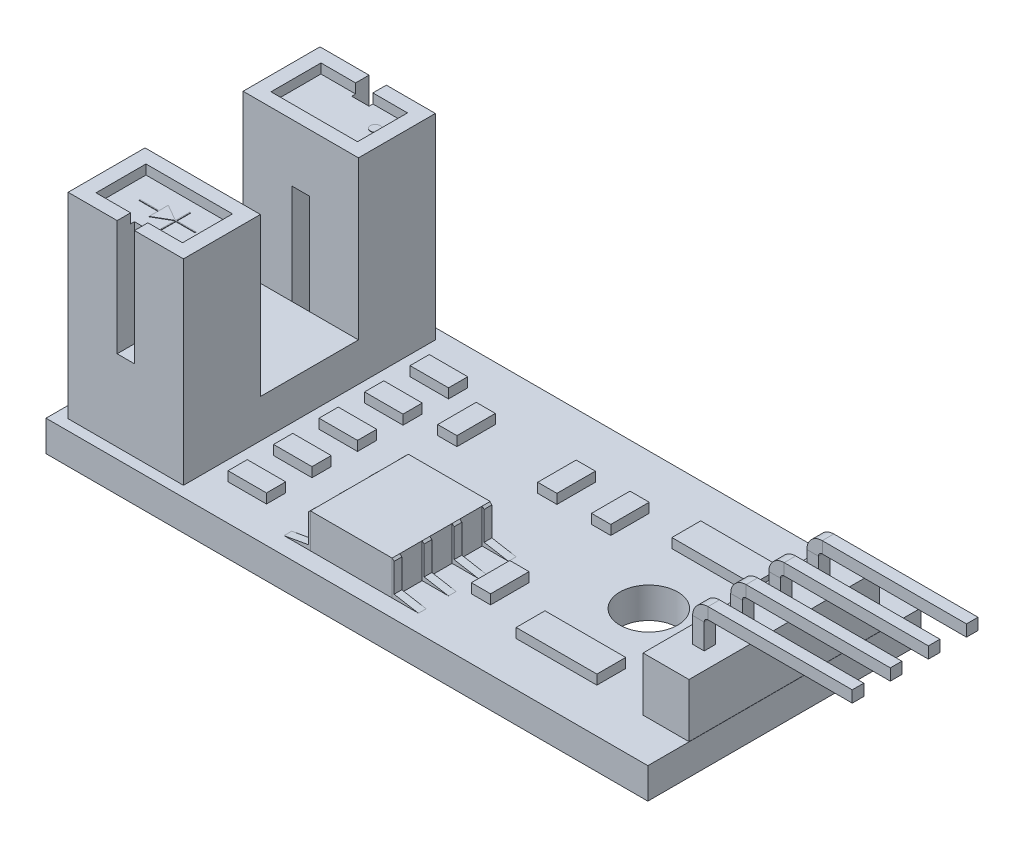
SolidWorks part; units mm, degrees
ref_plane "Front Plane" through (0, 0, 0) normal (0, 0, 1) x (1, 0, 0)
ref_plane "Top Plane" through (0, 0, 0) normal (0, 1, 0) x (1, 0, 0)
ref_plane "Right Plane" through (0, 0, 0) normal (1, 0, 0) x (0, 0, -1)
sketch "Sketch1" plane through (0, 0, 0) normal (0, 1, 0) x (1, 0, 0)
  line L1 (-15.65, 7.1) -> (15.65, 7.1)
  line L2 (-15.65, 7.1) -> (-15.65, -7.1)
  line L3 (-15.65, -7.1) -> (15.65, -7.1)
  line L4 (15.65, 7.1) -> (15.65, -7.1)
  line L5 (-15.65, 7.1) -> (15.65, -7.1) construction
  line L6 (-15.65, -7.1) -> (15.65, 7.1) construction
  point P0 (0, 0)
  dimension "D1" = 14.2
  dimension "D2" = 31.3
extrude "Boss-Extrude1" add sketch "Sketch1" along normal mid plane 1.6
sketch "Sketch2" plane through (0, 0.8, 0) normal (0, 1, 0) x (1, 0, 0)
  line L0 (-15.65, 7.1) -> (-15.65, -7.1) construction
  line L1 (-15.05, 6.55) -> (-9.05, 6.55)
  line L2 (-15.05, 6.55) -> (-15.05, -6.55)
  line L3 (-15.05, -6.55) -> (-9.05, -6.55)
  line L4 (-9.05, 6.55) -> (-9.05, -6.55)
  line L5 (-15.05, 6.55) -> (-9.05, -6.55) construction
  line L6 (-15.05, -6.55) -> (-9.05, 6.55) construction
  point P0 (-12.05, 0)
  dimension "D1" = 13.1
  dimension "D2" = 6
  dimension "D3" = 0.6
extrude "Boss-Extrude2" add sketch "Sketch2" along normal blind 2
sketch "Sketch3" plane through (0, 2.8, 0) normal (0, 1, 0) x (1, 0, 0)
  line L0 (-15.05, -6.55) -> (-9.05, -6.55) construction
  line L1 (-15.05, -2.55) -> (-9.05, -2.55)
  line L2 (-15.05, -2.55) -> (-15.05, -6.55)
  line L3 (-15.05, -6.55) -> (-9.05, -6.55)
  line L4 (-9.05, -2.55) -> (-9.05, -6.55)
  line L5 (-15.05, -2.55) -> (-9.05, -6.55) construction
  line L6 (-15.05, -6.55) -> (-9.05, -2.55) construction
  line L7 (-15.05, 6.55) -> (-15.05, -6.55) construction
  line L8 (-15.05, 6.55) -> (-9.05, 6.55)
  line L9 (-15.05, 6.55) -> (-15.05, 2.55)
  line L10 (-15.05, 2.55) -> (-9.05, 2.55)
  line L11 (-9.05, 6.55) -> (-9.05, 2.55)
  line L12 (-15.05, 6.55) -> (-9.05, 2.55) construction
  line L13 (-15.05, 2.55) -> (-9.05, 6.55) construction
  line L14 (-9.05, 6.55) -> (-15.05, 6.55) construction
  point P0 (-12.05, -4.55)
  point P9 (-12.05, 4.55)
  dimension "D1" = 4
  dimension "D2" = 6
  dimension "D3" = 4
  dimension "D4" = 6
extrude "Boss-Extrude3" add sketch "Sketch3" along normal blind 8.2
sketch "Sketch4" plane through (0, 0, 6.55) normal (0, 0, 1) x (1, 0, 0)
  line L0 (-15.05, 11) -> (-9.05, 11) construction
  line L1 (-12.5, 11) -> (-11.6, 11)
  line L2 (-12.5, 11) -> (-12.5, 5)
  line L3 (-12.5, 5) -> (-11.6, 5)
  line L4 (-11.6, 11) -> (-11.6, 5)
  line L5 (-12.5, 11) -> (-11.6, 5) construction
  line L6 (-12.5, 5) -> (-11.6, 11) construction
  point P0 (-12.05, 8)
  point P9 (-12.05, 11)
  dimension "D1" = 6
  dimension "D2" = 0.9
extrude "Cut-Extrude1" cut sketch "Sketch4" against normal blind 0.9
mirror "Mirror1" about plane through (0, 0, 0) normal (0, 0, 1) of "Cut-Extrude1"
sketch "Sketch5" plane through (0, 0, 2.55) normal (0, 0, -1) x (-1, 0, 0)
  line L0 (12.05, 11) -> (12.05, 8) construction
  line L1 (11.6, 11) -> (12.5, 11) construction
  line L2 (9.05, 0.8) -> (15.05, 0.8) construction
  line L3 (11.6, 0.8) -> (12.5, 0.8)
  line L4 (11.6, 0.8) -> (11.6, 8)
  line L5 (11.6, 8) -> (12.5, 8)
  line L6 (12.5, 0.8) -> (12.5, 8)
  line L7 (11.6, 0.8) -> (12.5, 8) construction
  line L8 (11.6, 8) -> (12.5, 0.8) construction
  point P4 (12.05, 4.4)
  dimension "D1" = 3
  dimension "D2" = 0.9
extrude "Cut-Extrude2" cut sketch "Sketch5" against normal blind 0.9
mirror "Mirror2" about plane through (0, 0, 0) normal (0, 0, 1) of "Cut-Extrude2"
sketch "Sketch6" plane through (0, 11, 0) normal (0, 1, 0) x (1, 0, 0)
  line L0 (-15.05, 6.55) -> (-9.05, 2.55) construction
  line L1 (-14.3, 5.85) -> (-9.8, 5.85)
  line L2 (-14.3, 5.85) -> (-14.3, 3.25)
  line L3 (-14.3, 3.25) -> (-9.8, 3.25)
  line L4 (-9.8, 5.85) -> (-9.8, 3.25)
  line L5 (-14.3, 5.85) -> (-9.8, 3.25) construction
  line L6 (-14.3, 3.25) -> (-9.8, 5.85) construction
  line L7 (-15.05, -2.55) -> (-9.05, -6.55) construction
  line L8 (-14.3, -3.25) -> (-9.8, -3.25)
  line L9 (-14.3, -3.25) -> (-14.3, -5.85)
  line L10 (-14.3, -5.85) -> (-9.8, -5.85)
  line L11 (-9.8, -3.25) -> (-9.8, -5.85)
  line L12 (-14.3, -3.25) -> (-9.8, -5.85) construction
  line L13 (-14.3, -5.85) -> (-9.8, -3.25) construction
  point P0 (-12.05, 4.55)
  point P11 (-12.05, -4.55)
  dimension "D1" = 2.6
  dimension "D2" = 4.5
  dimension "D3" = 2.6
  dimension "D4" = 4.5
extrude "Cut-Extrude3" cut sketch "Sketch6" against normal blind 0.5
sketch "Sketch7" plane through (0, -0.8, 0) normal (0, -1, 0) x (1, 0, 0)
  line L0 (-15.65, -7.1) -> (-15.65, 7.1) construction
  line L1 (-15.65, 0) -> (7.1, 0) construction
  circle A0 centre (8.6, 0) radius 1.5
  dimension "D1" = 3
  dimension "D2" = 22.75
extrude "Cut-Extrude4" cut sketch "Sketch7" against normal through all both and the other way through all
sketch "Sketch8" plane through (0, 0.8, 0) normal (0, 1, 0) x (1, 0, 0)
  line L0 (15.65, -7.1) -> (15.65, 7.1) construction
  line L1 (13.25, 4.95) -> (15.65, 4.95)
  line L2 (13.25, 4.95) -> (13.25, -4.95)
  line L3 (13.25, -4.95) -> (15.65, -4.95)
  line L4 (15.65, 4.95) -> (15.65, -4.95)
  line L5 (13.25, 4.95) -> (15.65, -4.95) construction
  line L6 (13.25, -4.95) -> (15.65, 4.95) construction
  point P0 (14.45, 0)
  dimension "D1" = 9.9
  dimension "D2" = 2.4
extrude "Boss-Extrude4" add sketch "Sketch8" along normal blind 2.8 separate body
sketch "Sketch9" plane through (0, 0.8, 0) normal (0, 1, 0) x (1, 0, 0)
  line L0 (-15.65, -7.1) -> (15.65, -7.1) construction
  line L1 (-2.8, -1.1) -> (1.45, -1.1)
  line L2 (-2.8, -1.1) -> (-2.8, -6.2)
  line L3 (-2.8, -6.2) -> (1.45, -6.2)
  line L4 (1.45, -1.1) -> (1.45, -6.2)
  line L5 (-2.8, -1.1) -> (1.45, -6.2) construction
  line L6 (-2.8, -6.2) -> (1.45, -1.1) construction
  line L7 (-9.05, -6.55) -> (-9.05, -2.55) construction
  point P0 (-0.675, -3.65)
  dimension "D1" = 5.1
  dimension "D2" = 4.25
  dimension "D3" = 0.9
  dimension "D4" = 6.25
extrude "Boss-Extrude5" add sketch "Sketch9" along normal blind 1.8
sketch "Sketch10" plane through (0, 3.6, 0) normal (0, 1, 0) x (1, 0, 0)
  line L0 (14.45, -4.95) -> (14.45, -2.97) construction
  line L1 (13.25, -4.95) -> (15.65, -4.95) construction
  line L2 (14.45, -2.97) -> (14.45, -0.99) construction
  line L3 (14.15, 3.27) -> (14.75, 3.27)
  line L4 (14.15, 1.29) -> (14.75, 1.29)
  line L5 (14.15, 1.29) -> (14.15, 0.69)
  line L6 (14.15, 0.69) -> (14.75, 0.69)
  line L7 (14.75, 1.29) -> (14.75, 0.69)
  line L8 (14.15, 1.29) -> (14.75, 0.69) construction
  line L9 (14.15, 0.69) -> (14.75, 1.29) construction
  line L10 (14.15, 3.27) -> (14.15, 2.67)
  line L11 (14.15, 2.67) -> (14.75, 2.67)
  line L12 (14.75, 3.27) -> (14.75, 2.67)
  line L13 (14.15, 3.27) -> (14.75, 2.67) construction
  line L14 (14.15, 2.67) -> (14.75, 3.27) construction
  line L15 (14.15, -2.67) -> (14.75, -2.67)
  line L16 (14.15, -2.67) -> (14.15, -3.27)
  line L17 (14.15, -3.27) -> (14.75, -3.27)
  line L18 (14.75, -2.67) -> (14.75, -3.27)
  line L19 (14.15, -2.67) -> (14.75, -3.27) construction
  line L20 (14.15, -3.27) -> (14.75, -2.67) construction
  line L21 (14.15, -0.69) -> (14.75, -0.69)
  line L22 (14.15, -0.69) -> (14.15, -1.29)
  line L23 (14.15, -1.29) -> (14.75, -1.29)
  line L24 (14.75, -0.69) -> (14.75, -1.29)
  line L25 (14.15, -0.69) -> (14.75, -1.29) construction
  line L26 (14.15, -1.29) -> (14.75, -0.69) construction
  line L28 (14.45, -0.99) -> (14.45, 0.99) construction
  line L29 (14.45, 0.99) -> (14.45, 2.97) construction
  line L30 (14.45, 2.97) -> (14.45, 4.95) construction
  line L31 (15.65, 4.95) -> (13.25, 4.95) construction
  point P6 (14.45, 0.99)
  point P11 (14.45, 2.97)
  point P16 (14.45, -2.97)
  point P21 (14.45, -0.99)
  dimension "D1" = 0.6
  dimension "D2" = 0.6
  dimension "D3" = 0.6
  dimension "D4" = 0.6
extrude "Cut-Extrude5" cut sketch "Sketch10" against normal through all both and the other way through all
sketch "Sketch11" plane through (0, 10.5, 0) normal (0, 1, 0) x (1, 0, 0)
  line L0 (-14.3, -5.85) -> (-9.8, -3.25) construction
  line L1 (-13.3387, -4.575) -> (-12.3387, -4.575)
  line L2 (-13.3387, -4.575) -> (-13.3387, -4.525)
  line L3 (-13.3387, -4.525) -> (-12.3387, -4.525)
  line L5 (-13.3387, -4.575) -> (-12.3387, -4.525) construction
  line L6 (-13.3387, -4.525) -> (-12.3387, -4.575) construction
  line L7 (-11.4905, -4.5397) -> (-12.3387, -4.05)
  line L8 (-12.3387, -4.05) -> (-12.3387, -4.525)
  line L9 (-12.3387, -5.05) -> (-11.4905, -4.5603)
  line L10 (-11.4226, -3.8) -> (-11.4726, -3.8)
  line L11 (-11.4226, -3.8) -> (-11.4226, -4.525)
  line L12 (-11.4226, -5.3) -> (-11.4726, -5.3)
  line L13 (-11.4726, -3.8) -> (-11.4726, -4.5397)
  line L14 (-11.4226, -3.8) -> (-11.4726, -5.3) construction
  line L15 (-11.4226, -5.3) -> (-11.4726, -3.8) construction
  line L16 (-10.4226, -4.525) -> (-11.4226, -4.525)
  line L17 (-10.4226, -4.525) -> (-10.4226, -4.575)
  line L18 (-10.4226, -4.575) -> (-11.4226, -4.575)
  line L20 (-10.4226, -4.525) -> (-11.4226, -4.575) construction
  line L21 (-10.4226, -4.575) -> (-11.4226, -4.525) construction
  line L22 (-11.4226, -4.575) -> (-11.4226, -5.3)
  line L23 (-12.3387, -4.575) -> (-12.3387, -5.05)
  line L24 (-11.4905, -4.5397) -> (-11.4726, -4.5397)
  line L25 (-11.4905, -4.5603) -> (-11.4726, -4.5603)
  line L26 (-11.4726, -4.5603) -> (-11.4726, -5.3)
  circle A0 centre (-12.05, -4.55) radius 0.2887 construction
  circle A1 centre (-10.4226, 4.7971) radius 0.25
  point P0 (-12.8387, -4.55)
  point P12 (-11.4476, -4.55)
  point P18 (-10.9226, -4.55)
  dimension "D4" = 0.5
  dimension "D1" = 1
  dimension "D2" = 0.05
  dimension "D3" = 1.5
extrude "Boss-Extrude11" add sketch "Sketch11" along normal blind 0.02
sketch "Sketch15" plane through (0, 0, 6.2) normal (0, 0, 1) x (1, 0, 0)
  line L0 (1.45, 0.8) -> (1.45, 2.6)
  line L1 (-15.65, 0.8) -> (15.65, 0.8) construction
  line L2 (1.45, 2.6) -> (1.45, 0.8) construction
  line L3 (-2.8, 2.6) -> (1.45, 2.6) construction
  line L4 (1.45, 2.6) -> (1.5556, 2.5036)
  line L5 (1.5556, 2.5036) -> (1.5556, 1.0228)
  line L6 (1.5556, 1.0228) -> (2.8211, 0.8)
  line L7 (2.8211, 0.8) -> (1.45, 0.8)
  line L8 (-0.675, 0.8) -> (-0.675, 2.6) construction
  line L9 (-2.8, 0.8) -> (1.45, 0.8) construction
  line L10 (-4.1711, 0.8) -> (-2.8, 0.8)
  line L11 (-2.9056, 1.0228) -> (-4.1711, 0.8)
  line L12 (-2.9056, 2.5036) -> (-2.9056, 1.0228)
  line L13 (-2.8, 2.6) -> (-2.9056, 2.5036)
  line L14 (-2.8, 0.8) -> (-2.8, 2.6)
extrude "Boss-Extrude14" add sketch "Sketch15" against normal blind 0.4 separate body
pattern_linear "LPattern1" count 4 spacing 1.56 along (0, 0, -1) of "Boss-Extrude14"
sketch "Sketch16" plane through (0, 0.8, 0) normal (0, 1, 0) x (1, 0, 0)
  line L0 (-8.05, -1.8667) -> (-6.05, -1.8667)
  line L1 (-8.05, -4.2333) -> (-6.05, -4.2333)
  line L2 (-8.05, -4.2333) -> (-8.05, -5.2333)
  line L3 (-8.05, -5.2333) -> (-6.05, -5.2333)
  line L4 (-6.05, -4.2333) -> (-6.05, -5.2333)
  line L5 (-8.05, -4.2333) -> (-6.05, -5.2333) construction
  line L6 (-8.05, -5.2333) -> (-6.05, -4.2333) construction
  line L7 (-8.05, -1.8667) -> (-8.05, -2.8667)
  line L8 (-8.05, -2.8667) -> (-6.05, -2.8667)
  line L9 (-6.05, -1.8667) -> (-6.05, -2.8667)
  line L10 (-8.05, -1.8667) -> (-6.05, -2.8667) construction
  line L11 (-8.05, -2.8667) -> (-6.05, -1.8667) construction
  line L12 (-8.05, 0.5) -> (-6.05, 0.5)
  line L13 (-8.05, 0.5) -> (-8.05, -0.5)
  line L14 (-8.05, -0.5) -> (-6.05, -0.5)
  line L15 (-6.05, 0.5) -> (-6.05, -0.5)
  line L16 (-8.05, 0.5) -> (-6.05, -0.5) construction
  line L17 (-8.05, -0.5) -> (-6.05, 0.5) construction
  line L18 (-8.05, 2.8667) -> (-6.05, 2.8667)
  line L19 (-8.05, 2.8667) -> (-8.05, 1.8667)
  line L20 (-8.05, 1.8667) -> (-6.05, 1.8667)
  line L21 (-6.05, 2.8667) -> (-6.05, 1.8667)
  line L22 (-8.05, 2.8667) -> (-6.05, 1.8667) construction
  line L23 (-8.05, 1.8667) -> (-6.05, 2.8667) construction
  line L24 (-8.05, 5.2333) -> (-6.05, 5.2333)
  line L25 (-8.05, 5.2333) -> (-8.05, 4.2333)
  line L26 (-8.05, 4.2333) -> (-6.05, 4.2333)
  line L27 (-6.05, 5.2333) -> (-6.05, 4.2333)
  line L28 (-8.05, 5.2333) -> (-6.05, 4.2333) construction
  line L29 (-8.05, 4.2333) -> (-6.05, 5.2333) construction
  line L30 (-7.05, 7.1) -> (-7.05, 4.7333) construction
  line L31 (15.65, 7.1) -> (-15.65, 7.1) construction
  line L32 (-7.05, 4.7333) -> (-7.05, 2.3667) construction
  line L33 (-7.05, 2.3667) -> (-7.05, 0) construction
  line L34 (-7.05, 0) -> (-7.05, -2.3667) construction
  line L35 (-7.05, -2.3667) -> (-7.05, -4.7333) construction
  line L36 (-7.05, -4.7333) -> (-7.05, -7.1) construction
  line L37 (-15.65, -7.1) -> (15.65, -7.1) construction
  line L38 (-9.05, -6.55) -> (-9.05, -2.55) construction
  line L39 (0.5211, 4.3) -> (1.5211, 4.3)
  line L40 (-4.6789, 4.3) -> (-3.6789, 4.3)
  line L41 (-4.6789, 4.3) -> (-4.6789, 2.3)
  line L42 (-4.6789, 2.3) -> (-3.6789, 2.3)
  line L43 (-3.6789, 4.3) -> (-3.6789, 2.3)
  line L44 (-4.6789, 4.3) -> (-3.6789, 2.3) construction
  line L45 (-4.6789, 2.3) -> (-3.6789, 4.3) construction
  line L46 (0.5211, 4.3) -> (0.5211, 2.3)
  line L47 (0.5211, 2.3) -> (1.5211, 2.3)
  line L48 (1.5211, 4.3) -> (1.5211, 2.3)
  line L49 (0.5211, 4.3) -> (1.5211, 2.3) construction
  line L50 (0.5211, 2.3) -> (1.5211, 4.3) construction
  line L51 (3.3211, 4.3) -> (4.3211, 4.3)
  line L52 (3.3211, 4.3) -> (3.3211, 2.3)
  line L53 (3.3211, 2.3) -> (4.3211, 2.3)
  line L54 (4.3211, 4.3) -> (4.3211, 2.3)
  line L55 (3.3211, 4.3) -> (4.3211, 2.3) construction
  line L56 (3.3211, 2.3) -> (4.3211, 4.3) construction
  line L57 (3.3211, -1.95) -> (4.3211, -1.95)
  line L58 (3.3211, -1.95) -> (3.3211, -3.95)
  line L59 (3.3211, -3.95) -> (4.3211, -3.95)
  line L60 (4.3211, -1.95) -> (4.3211, -3.95)
  line L61 (3.3211, -1.95) -> (4.3211, -3.95) construction
  line L62 (3.3211, -3.95) -> (4.3211, -1.95) construction
  line L63 (3.8211, -2.95) -> (3.8211, 3.3) construction
  line L64 (1.0211, 3.3) -> (3.8211, 3.3) construction
  line L65 (1.0211, 3.3) -> (-4.1789, 3.3) construction
  line L66 (2.8211, -2.68) -> (2.8211, -3.08) construction
  line L67 (6.5, -3.3) -> (10.7, -3.3)
  line L68 (6.5, 4.8) -> (10.7, 4.8)
  line L69 (6.5, 4.8) -> (6.5, 3.3)
  line L70 (6.5, 3.3) -> (10.7, 3.3)
  line L71 (10.7, 4.8) -> (10.7, 3.3)
  line L72 (6.5, 4.8) -> (10.7, 3.3) construction
  line L73 (6.5, 3.3) -> (10.7, 4.8) construction
  line L74 (6.5, -3.3) -> (6.5, -4.8)
  line L75 (6.5, -4.8) -> (10.7, -4.8)
  line L76 (10.7, -3.3) -> (10.7, -4.8)
  line L77 (6.5, -3.3) -> (10.7, -4.8) construction
  line L78 (6.5, -4.8) -> (10.7, -3.3) construction
  line L79 (8.6, 0) -> (8.6, 7.1) construction
  point P0 (-7.05, -4.7333)
  point P6 (-7.05, -2.3667)
  point P11 (-7.05, 0)
  point P16 (-7.05, 2.3667)
  point P21 (-7.05, 4.7333)
  point P37 (1.0211, 3.3)
  point P40 (-4.1789, 3.3)
  point P49 (3.8211, 3.3)
  point P54 (8.6, -4.05)
  point P56 (3.8211, -2.95)
  point P65 (8.6, 4.05)
  dimension "D1" = 1
  dimension "D2" = 2
  dimension "D3" = 1
  dimension "D4" = 2
  dimension "D5" = 1
  dimension "D6" = 2
  dimension "D7" = 1
  dimension "D8" = 2
  dimension "D9" = 1
  dimension "D10" = 2
  dimension "D11" = 1
  dimension "D12" = 2
  dimension "D13" = 1
  dimension "D14" = 2
  dimension "D15" = 1
  dimension "D16" = 2
  dimension "D17" = 1
  dimension "D18" = 2
  dimension "D19" = 1
  dimension "D20" = 6.25
  dimension "D21" = 2.8
  dimension "D22" = 1.8
  dimension "D23" = 4.2
  dimension "D24" = 0.5
  dimension "D25" = 1.5
  dimension "D26" = 4.2
  dimension "D27" = 1.5
  dimension "D28" = 4.2
  dimension "D29" = 3.8
  dimension "D30" = 3.8
extrude "Boss-Extrude15" add sketch "Sketch16" along normal blind 0.5
sketch "Sketch17" plane through (0, -0.8, 0) normal (0, -1, 0) x (1, 0, 0)
  line L0 (-13.65, 5.1) -> (-15.65, 5.1) construction
  line L1 (-13.65, 5.8) -> (-12.25, 5.8)
  line L2 (-13.65, 5.8) -> (-13.65, 4.4)
  line L3 (-13.65, 4.4) -> (-12.25, 4.4)
  line L4 (-12.25, 5.8) -> (-12.25, 4.4)
  line L5 (-13.65, 5.8) -> (-12.25, 4.4) construction
  line L6 (-13.65, 4.4) -> (-12.25, 5.8) construction
  line L7 (-15.65, -7.1) -> (-15.65, 7.1) construction
  line L8 (-12.95, 5.1) -> (-10.55, 5.1) construction
  line L9 (-15.65, 7.1) -> (15.65, 7.1) construction
  line L10 (-11.25, 5.8) -> (-9.85, 5.8)
  line L11 (-11.25, 5.8) -> (-11.25, 4.4)
  line L12 (-11.25, 4.4) -> (-9.85, 4.4)
  line L13 (-9.85, 5.8) -> (-9.85, 4.4)
  line L14 (-11.25, 5.8) -> (-9.85, 4.4) construction
  line L15 (-11.25, 4.4) -> (-9.85, 5.8) construction
  line L16 (0, 0) -> (-15.65, 0) construction
  line L17 (-11.25, -4.4) -> (-9.85, -5.8) construction
  line L18 (-11.25, -5.8) -> (-9.85, -4.4) construction
  line L19 (-12.95, -5.1) -> (-10.55, -5.1) construction
  line L20 (-13.65, -4.4) -> (-12.25, -5.8) construction
  line L21 (-13.65, -5.8) -> (-12.25, -4.4) construction
  line L22 (-13.65, -5.1) -> (-15.65, -5.1) construction
  line L23 (-9.85, -5.8) -> (-9.85, -4.4)
  line L24 (-11.25, -4.4) -> (-9.85, -4.4)
  line L25 (-11.25, -5.8) -> (-11.25, -4.4)
  line L26 (-11.25, -5.8) -> (-9.85, -5.8)
  line L27 (-12.25, -5.8) -> (-12.25, -4.4)
  line L28 (-13.65, -4.4) -> (-12.25, -4.4)
  line L29 (-13.65, -5.8) -> (-13.65, -4.4)
  line L30 (-13.65, -5.8) -> (-12.25, -5.8)
  point P0 (-12.95, 5.1)
  point P11 (-10.55, 5.1)
  dimension "D1" = 1.4
  dimension "D2" = 1.4
  dimension "D3" = 2.7
  dimension "D4" = 3.8
  dimension "D5" = 5.8
extrude "Cut-Extrude6" cut sketch "Sketch17" against normal up to surface (1.6 mm away) up to face at (-0.675, 0.8, 2.99)
sketch "Sketch18" plane through (0, 3.6, 0) normal (0, 1, 0) x (1, 0, 0)
  line L0 (14.15, -2.67) -> (14.75, -3.27) construction
  line L2 (14.15, -3.27) -> (14.75, -3.27)
  line L3 (14.15, -3.27) -> (14.15, -2.67)
  line L4 (14.15, -2.67) -> (14.75, -2.67)
  line L5 (14.75, -3.27) -> (14.75, -2.67)
  line L6 (14.15, -3.27) -> (14.75, -2.67) construction
  line L7 (14.15, -2.67) -> (14.75, -3.27) construction
  point P4 (14.45, -2.97)
ref_plane "Plane1" through (0, 0, 2.97) normal (0, 0, 1) x (1, 0, 0)
sketch "Sketch19" plane through (0, 0, 2.97) normal (0, 0, 1) x (1, 0, 0)
  line L0 (14.45, 3.6) -> (14.45, 4.9)
  line L1 (14.95, 5.4) -> (22.45, 5.4)
  line L2 (14.45, 3.6) -> (14.45, -1.3)
  line L4 (-15.65, -0.8) -> (15.65, -0.8) construction
  arc A0 (14.45, 4.9) -> (14.95, 5.4) centre (14.95, 4.9) cw
  point P7 (14.45, 5.4)
  dimension "D2" = 0.5
  dimension "D1" = 8
  dimension "D3" = 1.8
  dimension "D4" = 0.5
sweep "Sweep2" add profiles "Sketch18" path "Sketch19"
mirror "Mirror3" about plane through (0, 0, 0) normal (0, 0, 1) of "Sweep2"
sketch "Sketch20" plane through (15.65, 0, 0) normal (1, 0, 0) x (0, 0, -1)
  line L0 (4.95, 3.6) -> (-4.95, 3.6)
  line L1 (-4.95, 3.6) -> (-4.95, 0.8)
  line L2 (-4.95, 3.6) -> (-4.95, 0.8) construction
  line L3 (-4.95, 0.8) -> (4.95, 0.8)
  line L4 (4.95, 0.8) -> (4.95, 3.6)
extrude "Cut-Extrude7" cut sketch "Sketch20" against normal blind 0.01
sketch "Sketch21" plane through (0, 3.6, 0) normal (0, 1, 0) x (1, 0, 0)
  line L0 (14.15, -0.69) -> (14.75, -1.29) construction
  line L2 (14.15, -1.29) -> (14.75, -1.29)
  line L3 (14.15, -1.29) -> (14.15, -0.69)
  line L4 (14.15, -0.69) -> (14.75, -0.69)
  line L5 (14.75, -1.29) -> (14.75, -0.69)
  line L6 (14.15, -1.29) -> (14.75, -0.69) construction
  line L7 (14.15, -0.69) -> (14.75, -1.29) construction
  point P4 (14.45, -0.99)
ref_plane "Plane2" through (0, 0, 0.99) normal (0, 0, 1) x (1, 0, 0)
sketch "Sketch22" plane through (0, 0, 0.99) normal (0, 0, 1) x (1, 0, 0)
  line L0 (14.45, -1.3) -> (14.45, 4.9)
  line L1 (14.15, -1.3) -> (14.75, -1.3) construction
  line L2 (14.95, 5.4) -> (22.45, 5.4)
  line L3 (22.45, 5.7) -> (22.45, 5.1) construction
  line L4 (13.25, 3.6) -> (15.64, 3.6) construction
  arc A0 (14.95, 5.4) -> (14.45, 4.9) centre (14.95, 4.9) ccw
  dimension "D1" = 0.5
  dimension "D2" = 1.8
sweep "Sweep3" add profiles "Sketch21" path "Sketch22"
mirror "Mirror4" about plane through (0, 0, 0) normal (0, 0, 1) of "Sweep3"
